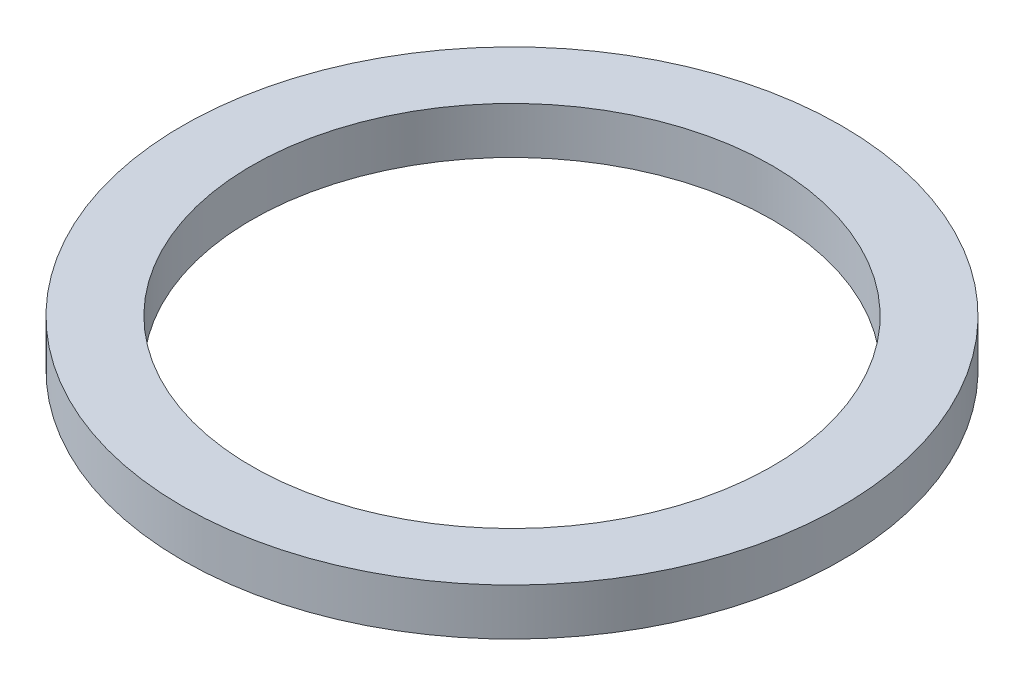
SolidWorks part; units mm, degrees
material "Copper"
ref_plane "Front Plane" through (0, 0, 0) normal (0, 0, 1) x (1, 0, 0)
ref_plane "Top Plane" through (0, 0, 0) normal (0, 1, 0) x (1, 0, 0)
ref_plane "Right Plane" through (0, 0, 0) normal (1, 0, 0) x (0, 0, -1)
sketch "Sketch1" plane through (0, 0, 0) normal (1, 0, 0) x (0, 0, -1)
  line L0 (0, 0) -> (0, 10.4189) construction
  line L2 (6.675, 1.2) -> (8.45, 1.2)
  line L3 (6.675, 1.2) -> (6.675, 0)
  line L4 (6.675, 0) -> (8.45, 0)
  line L5 (8.45, 1.2) -> (8.45, 0)
  dimension "D1" = 1.2
  dimension "D2" = 13.35
  dimension "D3" = 16.9
revolve "Revolve1" add sketch "Sketch1" angle 360 about L0
